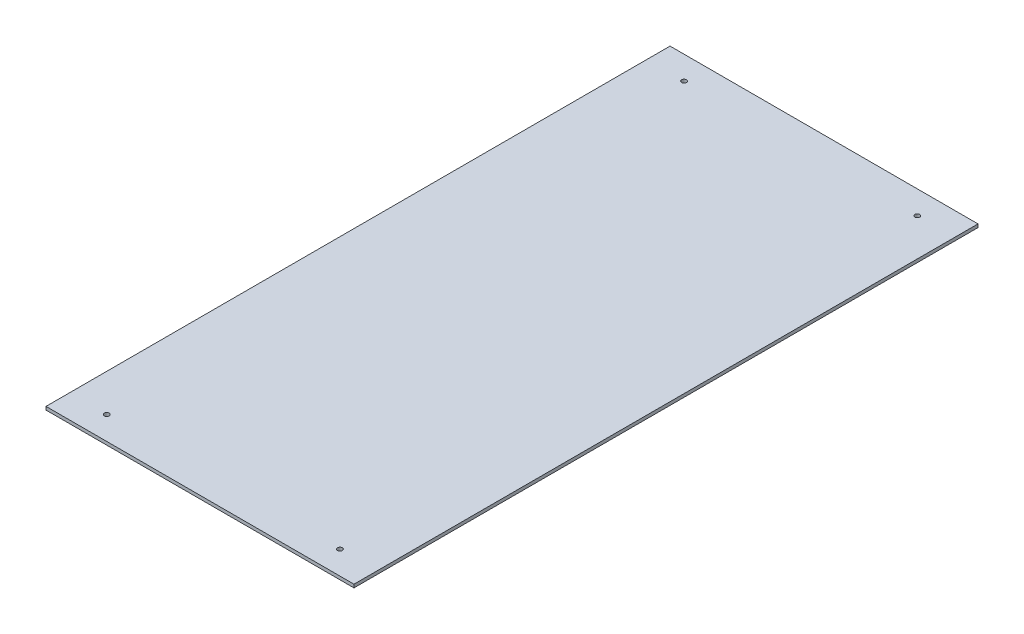
SolidWorks part; units mm, degrees
ref_plane "Front Plane" through (0, 0, 0) normal (0, 0, 1) x (1, 0, 0)
ref_plane "Top Plane" through (0, 0, 0) normal (0, 1, 0) x (1, 0, 0)
ref_plane "Right Plane" through (0, 0, 0) normal (1, 0, 0) x (0, 0, -1)
sketch "Sketch1" plane through (0, 0, 0) normal (0, 1, 0) x (1, 0, 0)
  line L0 (-74.93, -168.55) -> (74.93, -168.55) construction
  line L1 (-74.93, 181.61) -> (74.93, 181.61)
  line L2 (-74.93, 181.61) -> (-74.93, -181.61)
  line L3 (-74.93, -181.61) -> (74.93, -181.61)
  line L4 (74.93, 181.61) -> (74.93, -181.61)
  line L5 (-74.93, 181.61) -> (74.93, -181.61) construction
  line L6 (-74.93, -181.61) -> (74.93, 181.61) construction
  line L7 (-95, 192.5) -> (95, 192.5)
  line L8 (-95, 192.5) -> (-95, -192.5)
  line L9 (-95, -192.5) -> (95, -192.5)
  line L10 (95, 192.5) -> (95, -192.5)
  line L11 (-95, 192.5) -> (95, -192.5) construction
  line L12 (-95, -192.5) -> (95, 192.5) construction
  line L13 (64.77, -168.55) -> (64.77, -148.27) construction
  line L14 (0, 192.5) -> (0, -192.5) construction
  line L15 (-95, 0) -> (95, 0) construction
  circle A0 centre (-59.69, -168.55) radius 5
  circle A1 centre (-44.45, -168.55) radius 5
  circle A2 centre (-29.21, -168.55) radius 5
  circle A3 centre (-13.97, -168.55) radius 5
  circle A4 centre (1.27, -168.55) radius 5
  circle A5 centre (16.51, -168.55) radius 5
  circle A6 centre (31.75, -168.55) radius 5
  circle A7 centre (46.99, -168.55) radius 5
  circle A8 centre (64.77, -168.55) radius 5
  circle A9 centre (64.77, -148.27) radius 5
  circle A10 centre (-71.93, 178.11) radius 1.5
  circle A11 centre (71.93, 178.11) radius 1.5
  circle A12 centre (71.93, -178.11) radius 1.5
  circle A13 centre (-71.93, -178.11) radius 1.5
  point P0 (0, 0)
  point P5 (0, 0)
  dimension "D5" = 13.06
  dimension "D6" = 15.24
  dimension "D7" = 10
  dimension "D9" = 10
  dimension "D10" = 17.78
  dimension "D12" = 10
  dimension "D13" = 3
  dimension "D14" = 3
  dimension "D15" = 3.5
  dimension "D1" = 149.86
  dimension "D2" = 363.22
  dimension "D3" = 10.89
  dimension "D4" = 20.07
  dimension "D11" = 20.28
  dimension "D8" = 8
extrude "Boss-Extrude1" add sketch "Sketch1" along normal blind 2 contours L8 L7 L10 L9 | A13 | A12 | A11 | A10
